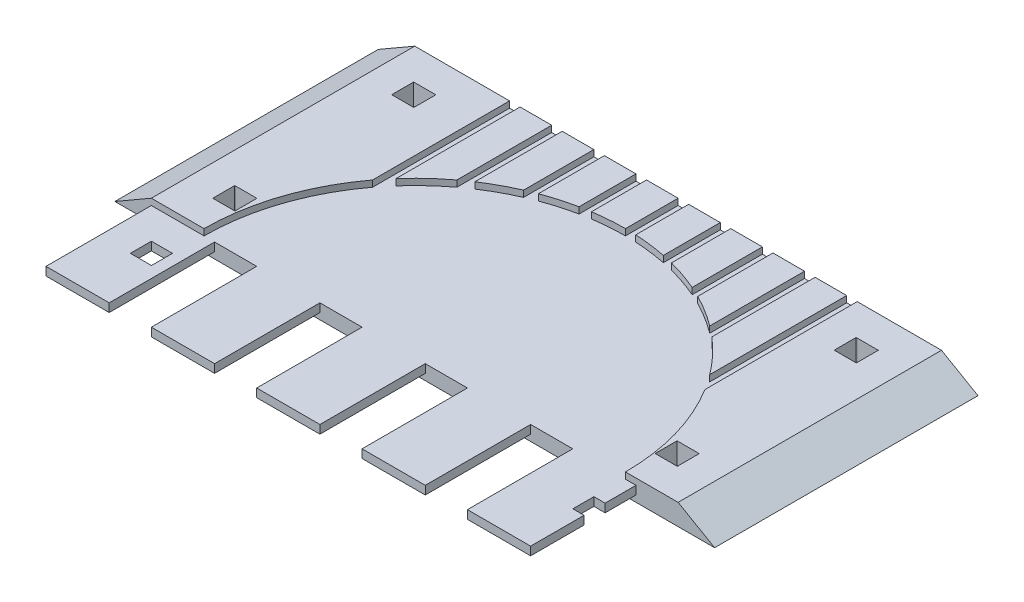
SolidWorks part; units mm, degrees
ref_plane "前视基准面" through (0, 0, 0) normal (0, 0, 1) x (1, 0, 0)
ref_plane "上视基准面" through (0, 0, 0) normal (0, 1, 0) x (1, 0, 0)
ref_plane "右视基准面" through (0, 0, 0) normal (1, 0, 0) x (0, 0, -1)
sketch "草图1" plane through (0, 0, 0) normal (0, 1, 0) x (1, 0, 0)
  line L0 (-125, 0) -> (125, 0)
  line L1 (-125, 125) -> (125, 125)
  line L2 (-125, 125) -> (-125, 0)
  line L4 (125, 125) -> (125, 0)
  line L5 (-125, 125) -> (125, -125) construction
  line L6 (-125, -125) -> (125, 125) construction
  point P0 (0, 0)
  dimension "D1" = 250
  dimension "D2" = 250
extrude "凸台-拉伸1" add sketch "草图1" along normal blind 10
sketch "草图2" plane through (0, 0, 0) normal (0, 0, 1) x (1, 0, 0)
  line L0 (-125, 7) -> (125, 7)
  line L1 (-75, 7) -> (-75, 3)
  line L2 (-125, 7) -> (-105, 7)
  line L3 (-125, 7) -> (-125, 3)
  line L4 (-125, 0) -> (125, 0)
  line L5 (125, 0) -> (125, 10)
  line L6 (125, 10) -> (-125, 10)
  line L7 (-125, 10) -> (-125, 0)
  line L8 (-125, 0) -> (125, 0)
  line L9 (125, 0) -> (125, 10)
  line L10 (125, 10) -> (-125, 10)
  line L11 (-125, 10) -> (-125, 0)
  line L12 (-125, 3) -> (-105, 3)
  line L13 (-105, 7) -> (-105, 3)
  line L14 (-105, 7) -> (-75, 7)
  line L15 (-105, 7) -> (-105, 3)
  line L16 (-105, 3) -> (-75, 3)
  line L17 (-75, 7) -> (-75, 3)
  line L18 (-75, 7) -> (-55, 7)
  line L19 (-55, 7) -> (-55, 3)
  line L20 (-75, 3) -> (-55, 3)
  line L21 (-55, 7) -> (-55, 3)
  line L22 (-55, 7) -> (-25, 7)
  line L23 (-25, 7) -> (-25, 3)
  line L24 (-55, 3) -> (-25, 3)
  line L25 (-25, 7) -> (-25, 3)
  line L26 (-25, 7) -> (-5, 7)
  line L27 (-5, 7) -> (-5, 3)
  line L28 (-25, 3) -> (-5, 3)
  line L29 (-5, 7) -> (-5, 3)
  line L30 (-5, 7) -> (25, 7)
  line L31 (25, 7) -> (25, 3)
  line L32 (-5, 3) -> (25, 3)
  line L33 (25, 7) -> (25, 3)
  line L34 (25, 7) -> (45, 7)
  line L35 (45, 7) -> (45, 3)
  line L36 (25, 3) -> (45, 3)
  line L37 (45, 7) -> (45, 3)
  line L38 (45, 7) -> (75, 7)
  line L39 (75, 7) -> (75, 3)
  line L40 (45, 3) -> (75, 3)
  line L41 (75, 7) -> (75, 3)
  line L42 (75, 7) -> (95, 7)
  line L43 (95, 7) -> (95, 3)
  line L44 (75, 3) -> (95, 3)
  line L45 (95, 7) -> (95, 3)
  line L46 (95, 7) -> (125, 7)
  line L47 (125, 7) -> (125, 3)
  line L48 (95, 3) -> (125, 3)
  dimension "D2" = 3
  dimension "D3" = 20
  dimension "D4" = 30
  dimension "D5" = 4
  dimension "D6" = 3
  dimension "D1" = 0
  dimension "D7" = 5
sketch "草图3" plane through (0, 10, 0) normal (0, 1, 0) x (1, 0, 0)
  line L0 (0, 125) -> (0, -49.5159)
  line L1 (-125, 125) -> (125, 125)
  line L2 (-125, 125) -> (-125, 0)
  line L3 (-125, 0) -> (125, 0)
  line L4 (125, 125) -> (125, 0)
  line L5 (-125, 125) -> (-105, 125)
  line L6 (-125, 125) -> (-125, 105)
  line L7 (-125, 105) -> (-105, 105)
  line L8 (-105, 125) -> (-105, 105)
  line L9 (-125, 0) -> (-105, 0)
  line L10 (-125, 0) -> (-125, 20)
  line L11 (-125, 20) -> (-105, 20)
  line L12 (-105, 0) -> (-105, 20)
  line L21 (-110, 110) -> (-100, 110)
  line L22 (-110, 110) -> (-110, 100)
  line L23 (-110, 100) -> (-100, 100)
  line L24 (-100, 110) -> (-100, 100)
  line L25 (-110, 110) -> (-100, 100) construction
  line L26 (-110, 100) -> (-100, 110) construction
  line L27 (-110, 25) -> (-100, 25)
  line L28 (-110, 25) -> (-110, 15)
  line L29 (-110, 15) -> (-100, 15)
  line L30 (-100, 25) -> (-100, 15)
  line L31 (-110, 25) -> (-100, 15) construction
  line L32 (-110, 15) -> (-100, 25) construction
  line L37 (112.5, 12.5) -> (97.5, 27.5) construction
  line L38 (112.5, 27.5) -> (97.5, 12.5) construction
  line L43 (115, 95) -> (95, 115) construction
  line L44 (115, 115) -> (95, 95) construction
  line L45 (-115, 115) -> (-95, 115)
  line L46 (-115, 115) -> (-115, 95)
  line L47 (-115, 95) -> (-95, 95)
  line L48 (-95, 115) -> (-95, 95)
  line L49 (-115, 115) -> (-95, 95) construction
  line L50 (-115, 95) -> (-95, 115) construction
  line L51 (-112.5, 27.5) -> (-97.5, 27.5)
  line L52 (-112.5, 27.5) -> (-112.5, 12.5)
  line L53 (-112.5, 12.5) -> (-97.5, 12.5)
  line L54 (-97.5, 27.5) -> (-97.5, 12.5)
  line L55 (-112.5, 27.5) -> (-97.5, 12.5) construction
  line L56 (-112.5, 12.5) -> (-97.5, 27.5) construction
  line L57 (110, 15) -> (100, 25) construction
  line L58 (110, 25) -> (100, 15) construction
  line L59 (110, 100) -> (100, 110) construction
  line L60 (110, 110) -> (100, 100) construction
  line L61 (97.5, 27.5) -> (97.5, 12.5)
  line L62 (112.5, 12.5) -> (97.5, 12.5)
  line L63 (112.5, 27.5) -> (112.5, 12.5)
  line L64 (112.5, 27.5) -> (97.5, 27.5)
  line L65 (95, 115) -> (95, 95)
  line L66 (115, 95) -> (95, 95)
  line L67 (115, 115) -> (115, 95)
  line L68 (115, 115) -> (95, 115)
  line L69 (100, 25) -> (100, 15)
  line L70 (110, 15) -> (100, 15)
  line L71 (110, 25) -> (110, 15)
  line L72 (110, 25) -> (100, 25)
  line L73 (100, 110) -> (100, 100)
  line L74 (110, 100) -> (100, 100)
  line L75 (110, 110) -> (110, 100)
  line L76 (110, 110) -> (100, 110)
  line L77 (105, 0) -> (105, 20)
  line L78 (125, 20) -> (105, 20)
  line L79 (125, 0) -> (125, 20)
  line L80 (125, 0) -> (105, 0)
  line L81 (105, 125) -> (105, 105)
  line L82 (125, 105) -> (105, 105)
  line L83 (125, 125) -> (125, 105)
  line L84 (125, 125) -> (105, 125)
  line L85 (125, 125) -> (125, 0)
  dimension "D1" = 20
  dimension "D2" = 20
  dimension "D3" = 20
  dimension "D4" = 20
  dimension "D9" = 10
  dimension "D10" = 10
  dimension "D11" = 10
  dimension "D12" = 10
  dimension "D17" = 20
  dimension "D18" = 20
  dimension "D19" = 15
  dimension "D20" = 15
sketch "草图4" plane through (0, 10, 0) normal (0, 1, 0) x (1, 0, 0)
  circle A0 centre (0, 0) radius 100
sketch "草图5" plane through (0, 10, 0) normal (0, 1, 0) x (1, 0, 0)
  line L1 (-110, 110) -> (-100, 110)
  line L2 (-110, 110) -> (-110, 100)
  line L3 (-110, 100) -> (-100, 100)
  line L4 (-100, 110) -> (-100, 100)
  line L5 (-110, 25) -> (-100, 25)
  line L6 (-110, 25) -> (-110, 15)
  line L7 (-110, 15) -> (-100, 15)
  line L8 (-100, 25) -> (-100, 15)
  line L9 (100, 110) -> (110, 110)
  line L10 (100, 110) -> (100, 100)
  line L11 (100, 100) -> (110, 100)
  line L12 (110, 110) -> (110, 100)
  line L13 (100, 25) -> (110, 25)
  line L14 (100, 25) -> (100, 15)
  line L15 (100, 15) -> (110, 15)
  line L16 (110, 25) -> (110, 15)
  point P25 (0, 0)
extrude "切除-拉伸1" cut sketch "草图5" against normal up to surface (10 mm away) up to face at (0, 0, -62.5)
sketch "草图6" plane through (0, 10, 0) normal (0, 1, 0) x (1, 0, 0)
  line L0 (-100, 0) -> (100, 0)
  arc A0 (100, 0) -> (-100, 0) centre (0, 0) ccw
extrude "切除-拉伸2" cut sketch "草图6" against normal blind 3
sketch "草图7" plane through (0, 0, 0) normal (0, 0, 1) x (1, 0, 0)
  line L0 (0, 7) -> (0, -25.8952)
  line L1 (-105, 7) -> (-75, 7)
  line L2 (-105, 7) -> (-105, 3)
  line L3 (-105, 3) -> (-75, 3)
  line L4 (-75, 7) -> (-75, 3)
  line L5 (-55, 7) -> (-25, 7)
  line L6 (-55, 7) -> (-55, 3)
  line L7 (-55, 3) -> (-25, 3)
  line L8 (-25, 7) -> (-25, 3)
  line L9 (-5, 7) -> (25, 7)
  line L10 (-5, 7) -> (-5, 3)
  line L11 (-5, 3) -> (25, 3)
  line L12 (25, 7) -> (25, 3)
  line L13 (45, 7) -> (75, 7)
  line L14 (45, 7) -> (45, 3)
  line L15 (45, 3) -> (75, 3)
  line L16 (75, 7) -> (75, 3)
  line L17 (95, 7) -> (125, 7)
  line L18 (95, 7) -> (95, 3)
  line L19 (95, 3) -> (125, 3)
  line L20 (125, 7) -> (125, 3)
sketch "草图8" plane through (0, 0, 0) normal (0, 0, 1) x (1, 0, 0)
  line L16 (-125, 7) -> (-95, 7)
  line L17 (-125, 3) -> (-125, 7)
  line L18 (-95, 3) -> (-125, 3)
  line L19 (-95, 7) -> (-95, 3)
  line L20 (-75, 7) -> (-45, 7)
  line L21 (-75, 3) -> (-75, 7)
  line L22 (-45, 3) -> (-75, 3)
  line L23 (-45, 7) -> (-45, 3)
  line L24 (-25, 7) -> (-25, 3)
  line L27 (5, 7) -> (5, 3)
  line L40 (55, 3) -> (25, 3)
  line L41 (25, 7) -> (25, 3)
  line L42 (55, 7) -> (25, 7)
  line L43 (55, 7) -> (55, 3)
  line L44 (105, 3) -> (75, 3)
  line L45 (75, 7) -> (75, 3)
  line L46 (105, 7) -> (75, 7)
  line L47 (105, 7) -> (105, 3)
  line L48 (-25, 7) -> (5, 7)
  line L49 (-25, 3) -> (5, 3)
extrude "凸台-拉伸2" add sketch "草图8" along normal blind 50
sketch "草图9" plane through (0, 7, 0) normal (0, 1, 0) x (1, 0, 0)
  line L1 (-110.323, -14.6462) -> (-100.323, -14.6462)
  line L2 (-110.323, -14.6462) -> (-110.323, -24.6462)
  line L3 (-110.323, -24.6462) -> (-100.323, -24.6462)
  line L4 (-100.323, -14.6462) -> (-100.323, -24.6462)
  line L5 (99.677, -14.6462) -> (104.677, -14.6462)
  line L6 (99.677, -14.6462) -> (99.677, -24.6462)
  line L7 (99.677, -24.6462) -> (104.677, -24.6462)
  line L8 (104.677, -14.6462) -> (104.677, -24.6462)
  line L18 (99.677, 0.3538) -> (124.677, 0.3538)
  line L19 (124.677, 0.3538) -> (124.677, 125.3538)
  line L20 (124.677, 125.3538) -> (-125.323, 125.3538)
  line L21 (-125.323, 125.3538) -> (-125.323, 0.3538)
  line L22 (-125.323, 0.3538) -> (-100.323, 0.3538)
  line L50 (-100.323, 0.3538) -> (-125.323, 0.3538)
  line L51 (-125.323, 0.3538) -> (-125.323, -49.6462)
  line L52 (-125.323, -49.6462) -> (-95.323, -49.6462)
  line L53 (-95.323, -49.6462) -> (-95.323, 0.3538)
  line L54 (-95.323, 0.3538) -> (-75.323, 0.3538)
  line L55 (-75.323, 0.3538) -> (-75.323, -49.6462)
  line L56 (-75.323, -49.6462) -> (-45.323, -49.6462)
  line L57 (-45.323, -49.6462) -> (-45.323, 0.3538)
  line L58 (-45.323, 0.3538) -> (-25.323, 0.3538)
  line L59 (-25.323, 0.3538) -> (-25.323, -49.6462)
  line L60 (-25.323, -49.6462) -> (4.677, -49.6462)
  line L61 (4.677, -49.6462) -> (4.677, 0.3538)
  line L62 (4.677, 0.3538) -> (24.677, 0.3538)
  line L63 (24.677, 0.3538) -> (24.677, -49.6462)
  line L64 (24.677, -49.6462) -> (54.677, -49.6462)
  line L65 (54.677, -49.6462) -> (54.677, 0.3538)
  line L66 (54.677, 0.3538) -> (74.677, 0.3538)
  line L67 (74.677, 0.3538) -> (74.677, -49.6462)
  line L68 (74.677, -49.6462) -> (104.677, -49.6462)
  line L69 (104.677, -49.6462) -> (104.677, 0.3538)
  line L70 (104.677, 0.3538) -> (99.677, 0.3538)
  arc A2 (99.677, 0.3538) -> (-100.323, 0.3538) centre (-0.323, 0.3538) ccw
  arc A4 (99.677, 0.3538) -> (-100.323, 0.3538) centre (-0.323, 0.3538) ccw
sketch "草图11" plane through (0, 10, 0) normal (0, 1, 0) x (1, 0, 0)
  line L0 (104.677, -14.6462) -> (112.2339, -14.6462)
  line L1 (-110.323, -14.6462) -> (-100.323, -14.6462)
  line L2 (-110.323, -14.6462) -> (-110.323, -24.6462)
  line L3 (-110.323, -24.6462) -> (-100.323, -24.6462)
  line L4 (-100.323, -14.6462) -> (-100.323, -24.6462)
  line L5 (99.677, -14.6462) -> (104.677, -14.6462)
  line L6 (99.677, -14.6462) -> (99.677, -24.6462)
  line L7 (99.677, -24.6462) -> (104.677, -24.6462)
  line L9 (112.2339, -14.6462) -> (112.2339, -24.6462)
  line L10 (112.2339, -24.6462) -> (104.677, -24.6462)
extrude "切除-拉伸4" cut sketch "草图11" against normal up to surface (10 mm away) up to face at (-105, 0, -20)
sketch "草图12" plane through (0, 10, 0) normal (0, 1, 0) x (1, 0, 0)
  line L2 (-80, 131.0287) -> (-75, 131.0287)
  line L3 (85, 131.0287) -> (85, 52.6783)
  line L4 (80, 131.0287) -> (80, 60)
  line L5 (65, 131.0287) -> (65, 75.9934)
  line L6 (60, 131.0287) -> (60, 80)
  line L7 (45, 131.0287) -> (45, 89.3029)
  line L8 (40, 131.0287) -> (40, 91.6515)
  line L9 (25, 131.0287) -> (25, 96.8246)
  line L10 (20, 131.0287) -> (20, 97.9796)
  line L11 (5, 131.0287) -> (5, 99.8749)
  line L12 (0, 131.0287) -> (0, 100)
  line L13 (-15, 131.0287) -> (-15, 98.8686)
  line L14 (-20, 131.0287) -> (-20, 97.9796)
  line L15 (-35, 131.0287) -> (-35, 93.675)
  line L16 (-40, 131.0287) -> (-40, 91.6515)
  line L17 (-55, 131.0287) -> (-55, 83.5165)
  line L18 (-60, 131.0287) -> (-60, 80)
  line L19 (-75, 131.0287) -> (-75, 66.1438)
  line L20 (-80, 131.0287) -> (-80, 60)
  line L21 (-60, 131.0287) -> (-55, 131.0287)
  line L23 (-95, 131.0287) -> (-95, 52.6783) [skipped]
  line L24 (-100, 131.0287) -> (-100, 60) [skipped]
  line L25 (-40, 131.0287) -> (-35, 131.0287)
  line L26 (-20, 131.0287) -> (-15, 131.0287)
  line L27 (0, 131.0287) -> (5, 131.0287)
  line L28 (20, 131.0287) -> (25, 131.0287)
  line L29 (40, 131.0287) -> (45, 131.0287)
  line L30 (60, 131.0287) -> (65, 131.0287)
  line L31 (80, 131.0287) -> (85, 131.0287)
  circle A0 centre (0, 0) radius 100 construction
  arc A1 (85, 52.6783) -> (80, 60) centre (0, 0) ccw
  arc A2 (-75, 66.1438) -> (-80, 60) centre (0, 0) ccw
  arc A3 (-55, 83.5165) -> (-60, 80) centre (0, 0) ccw
  arc A4 (-35, 93.675) -> (-40, 91.6515) centre (0, 0) ccw
  arc A5 (-15, 98.8686) -> (-20, 97.9796) centre (0, 0) ccw
  arc A6 (5, 99.8749) -> (0, 100) centre (0, 0) ccw
  arc A7 (25, 96.8246) -> (20, 97.9796) centre (0, 0) ccw
  arc A8 (45, 89.3029) -> (40, 91.6515) centre (0, 0) ccw
  arc A9 (65, 75.9934) -> (60, 80) centre (0, 0) ccw
  dimension "D2" = 5
  dimension "D3" = 10
extrude "切除-拉伸5" cut sketch "草图12" against normal up to surface (3 mm away) up to face at (-105.323, 7, 19.6462)
sketch "草图13" plane through (0, 0, -125) normal (0, 0, -1) x (-1, 0, 0)
  line L0 (125, 10) -> (125, 0)
  line L1 (125, 0) -> (142.3205, 0)
  line L2 (142.3205, 0) -> (125, 10)
  line L3 (-125, 10) -> (-125, 0)
  line L4 (-125, 0) -> (-142.3205, 0)
  line L5 (-142.3205, 0) -> (-125, 10)
  dimension "D1" = 30
  dimension "D2" = 30
extrude "凸台-拉伸3" add sketch "草图13" against normal up to surface (125 mm away) up to face at (10.4167, 5, 0)
sketch "草图14" plane through (0, 0, 0) normal (0, -1, 0) x (1, 0, 0)
  line L0 (-92.3205, -125) -> (-92.3205, -55.4041)
  line L1 (-92.3205, -55.4041) -> (-62.3205, -55.4041)
  line L2 (-62.3205, -55.4041) -> (-62.3205, -125)
  line L3 (-92.3205, -125) -> (-62.3205, -125)
  line L4 (-17.3205, -125) -> (12.6795, -125)
  line L5 (12.6795, -55.4041) -> (12.6795, -125)
  line L6 (-17.3205, -55.4041) -> (12.6795, -55.4041)
  line L7 (-17.3205, -125) -> (-17.3205, -55.4041)
  line L12 (57.6795, -125) -> (87.6795, -125)
  line L13 (87.6795, -55.4041) -> (87.6795, -125)
  line L14 (57.6795, -55.4041) -> (87.6795, -55.4041)
  line L15 (57.6795, -125) -> (57.6795, -55.4041)
  dimension "D3" = 30
  dimension "D1" = 3
extrude "切除-拉伸6" cut sketch "草图14" against normal blind 5
sketch "草图15" plane through (0, 0, 0) normal (0, -1, 0) x (1, 0, 0)
  line L4 (57.6795, -125) -> (87.6795, -125)
  line L5 (87.6795, -125) -> (87.6795, -55.4041)
  line L6 (87.6795, -55.4041) -> (57.6795, -55.4041)
  line L7 (57.6795, -55.4041) -> (57.6795, -125)
  line L8 (57.6795, -125) -> (87.6795, -125)
  line L9 (87.6795, -125) -> (87.6795, -55.4041)
  line L10 (87.6795, -55.4041) -> (57.6795, -55.4041)
  line L11 (57.6795, -55.4041) -> (57.6795, -125)
  line L12 (-17.3205, -125) -> (12.6795, -125)
  line L13 (12.6795, -125) -> (12.6795, -55.4041)
  line L14 (12.6795, -55.4041) -> (-17.3205, -55.4041)
  line L15 (-17.3205, -55.4041) -> (-17.3205, -125)
  line L16 (-17.3205, -125) -> (12.6795, -125)
  line L17 (12.6795, -125) -> (12.6795, -55.4041)
  line L18 (12.6795, -55.4041) -> (-17.3205, -55.4041)
  line L19 (-17.3205, -55.4041) -> (-17.3205, -125)
  line L20 (-92.3205, -55.4041) -> (-92.3205, -125)
  line L21 (-62.3205, -55.4041) -> (-92.3205, -55.4041)
  line L22 (-62.3205, -125) -> (-62.3205, -55.4041)
  line L23 (-92.3205, -125) -> (-62.3205, -125)
  line L24 (-92.3205, -55.4041) -> (-92.3205, -125)
  line L25 (-62.3205, -55.4041) -> (-92.3205, -55.4041)
  line L26 (-62.3205, -125) -> (-62.3205, -55.4041)
  line L27 (-92.3205, -125) -> (-62.3205, -125)
  line L40 (-142.3205, -125) -> (-92.3205, -125)
  line L41 (-92.3205, -125) -> (-92.3205, -55.4041)
  line L42 (-92.3205, -55.4041) -> (-62.3205, -55.4041)
  line L43 (-62.3205, -55.4041) -> (-62.3205, -125)
  line L44 (-62.3205, -125) -> (-17.3205, -125)
  line L45 (-17.3205, -125) -> (-17.3205, -55.4041)
  line L46 (-17.3205, -55.4041) -> (12.6795, -55.4041)
  line L47 (12.6795, -55.4041) -> (12.6795, -125)
  line L48 (12.6795, -125) -> (57.6795, -125)
  line L49 (57.6795, -125) -> (57.6795, -55.4041)
  line L50 (57.6795, -55.4041) -> (87.6795, -55.4041)
  line L51 (87.6795, -55.4041) -> (87.6795, -125)
  line L52 (87.6795, -125) -> (142.3205, -125)
  line L53 (142.3205, -125) -> (142.3205, 0)
  line L54 (142.3205, 0) -> (-142.3205, 0)
  line L55 (-142.3205, 0) -> (-142.3205, -125)
  line L56 (-142.3205, -125) -> (-92.3205, -125)
  line L57 (-92.3205, -125) -> (-92.3205, -55.4041)
  line L58 (-92.3205, -55.4041) -> (-62.3205, -55.4041)
  line L59 (-62.3205, -55.4041) -> (-62.3205, -125)
  line L60 (-62.3205, -125) -> (-17.3205, -125)
  line L61 (-17.3205, -125) -> (-17.3205, -55.4041)
  line L62 (-17.3205, -55.4041) -> (12.6795, -55.4041)
  line L63 (12.6795, -55.4041) -> (12.6795, -125)
  line L64 (12.6795, -125) -> (57.6795, -125)
  line L65 (57.6795, -125) -> (57.6795, -55.4041)
  line L66 (57.6795, -55.4041) -> (87.6795, -55.4041)
  line L67 (87.6795, -55.4041) -> (87.6795, -125)
  line L68 (87.6795, -125) -> (142.3205, -125)
  line L69 (142.3205, -125) -> (142.3205, 0)
  line L70 (142.3205, 0) -> (-142.3205, 0)
  line L71 (-142.3205, 0) -> (-142.3205, -125)
  dimension "D1" = 0
  dimension "D2" = 0
  dimension "D3" = 0
  dimension "D4" = 0
sketch "草图16" plane through (0, 10, 0) normal (0, 1, 0) x (1, 0, 0)
  line L1 (-100, 110) -> (-110.5174, 110)
  line L2 (-100, 110) -> (-100, 99.5766)
  line L3 (-100, 99.5766) -> (-110.5174, 99.5766)
  line L4 (-110.5174, 110) -> (-110.5174, 99.5766)
  line L5 (109.9797, 25.0347) -> (99.4623, 25.0347)
  line L6 (109.9797, 25.0347) -> (109.9797, 14.6113)
  line L7 (109.9797, 14.6113) -> (99.4623, 14.6113)
  line L8 (99.4623, 25.0347) -> (99.4623, 14.6113)
  line L9 (-99.8962, 24.9877) -> (-110.4136, 24.9877)
  line L10 (-99.8962, 24.9877) -> (-99.8962, 14.5643)
  line L11 (-99.8962, 14.5643) -> (-110.4136, 14.5643)
  line L12 (-110.4136, 24.9877) -> (-110.4136, 14.5643)
  line L13 (110.0037, 109.9988) -> (99.4863, 109.9988)
  line L14 (110.0037, 109.9988) -> (110.0037, 99.5754)
  line L15 (110.0037, 99.5754) -> (99.4863, 99.5754)
  line L16 (99.4863, 109.9988) -> (99.4863, 99.5754)
extrude "切除-拉伸7" cut sketch "草图16" against normal through all
